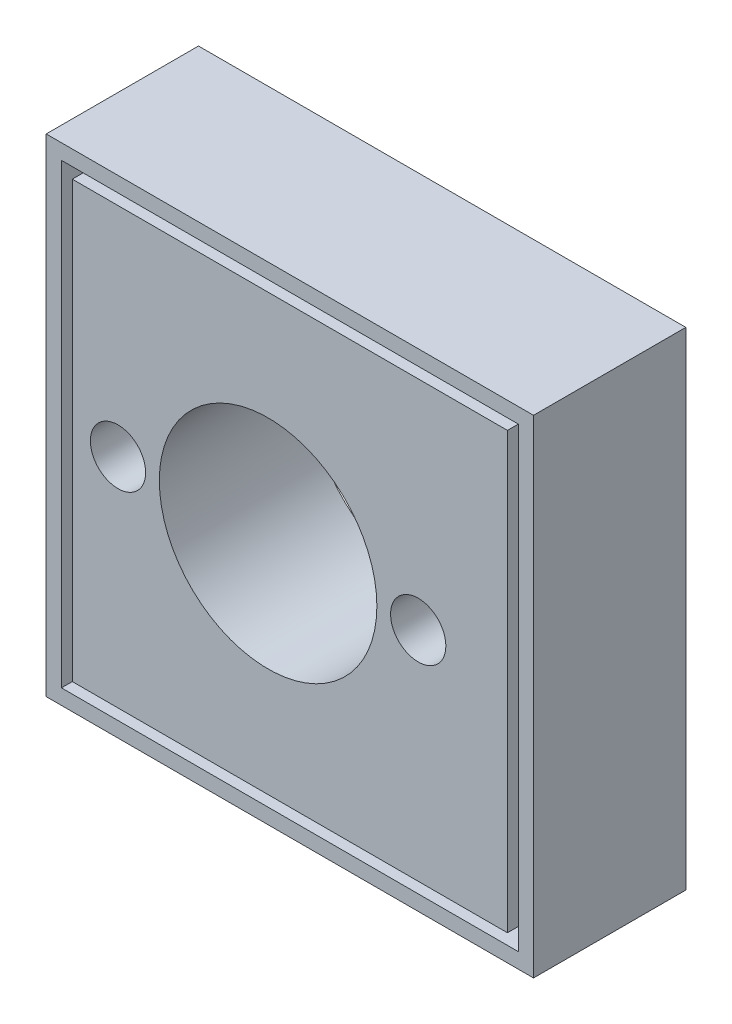
SolidWorks part; units mm, degrees
ref_plane "Front Plane" through (0, 0, 0) normal (0, 0, 1) x (1, 0, 0)
ref_plane "Top Plane" through (0, 0, 0) normal (0, 1, 0) x (1, 0, 0)
ref_plane "Right Plane" through (0, 0, 0) normal (1, 0, 0) x (0, 0, -1)
sketch "Sketch2" plane through (0, 0, 0) normal (0, 0, 1) x (1, 0, 0)
  line L1 (-56, -56) -> (56, -56)
  line L2 (-56, -56) -> (-56, 56)
  line L3 (-56, 56) -> (56, 56)
  line L4 (56, -56) -> (56, 56)
  line L5 (-56, -56) -> (56, 56) construction
  line L6 (-56, 56) -> (56, -56) construction
  circle A1 centre (-5, 0) radius 25
  point P0 (0, 0)
  dimension "D4" = 50
  dimension "D2" = 112
  dimension "D3" = 112
  dimension "D5" = 5
extrude "Boss-Extrude1" add sketch "Sketch2" along normal blind 15
sketch "Sketch3" plane through (0, 0, 15) normal (0, 0, 1) x (1, 0, 0)
  line L1 (-50, 50) -> (50, 50)
  line L2 (-50, 50) -> (-50, -50)
  line L3 (-50, -50) -> (50, -50)
  line L4 (50, 50) -> (50, -50)
  line L5 (-50, 50) -> (50, -50) construction
  line L6 (-50, -50) -> (50, 50) construction
  line L8 (-52.5, -52.5) -> (52.5, -52.5)
  line L9 (-52.5, -52.5) -> (-52.5, 52.5)
  line L10 (-52.5, 52.5) -> (52.5, 52.5)
  line L11 (52.5, -52.5) -> (52.5, 52.5)
  line L12 (-52.5, -52.5) -> (52.5, 52.5) construction
  line L13 (-52.5, 52.5) -> (52.5, -52.5) construction
  circle A0 centre (-39.5, 0) radius 6.35
  circle A3 centre (29.5, 0) radius 6.35
  point P4 (0, 0)
  point P12 (0, 0)
  dimension "D3" = 12.7
  dimension "D4" = 105
  dimension "D7" = 12.7
  dimension "D1" = 100
  dimension "D2" = 100
  dimension "D5" = 39.5
  dimension "D6" = 105
  dimension "D8" = 29.5
extrude "Boss-Extrude2" add sketch "Sketch3" along normal blind 20
